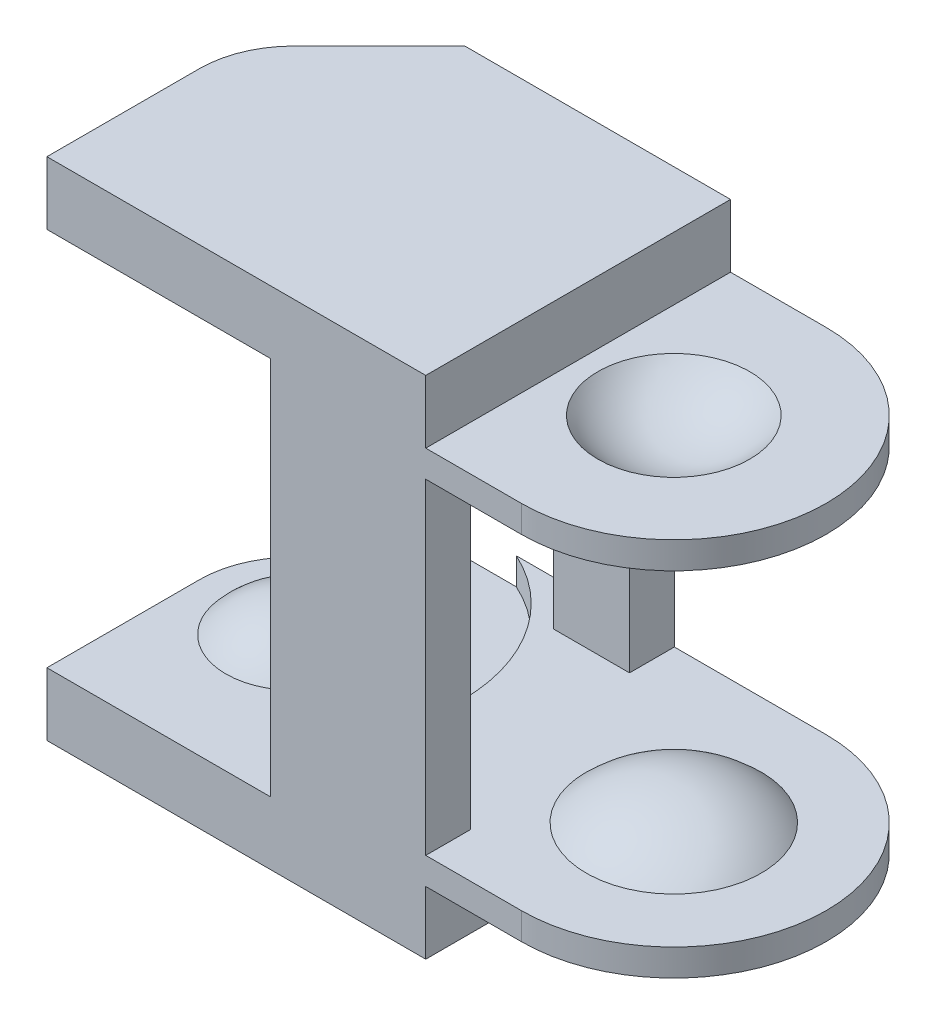
SolidWorks part; units mm, degrees
ref_plane "Front Plane" through (0, 0, 0) normal (0, 0, 1) x (1, 0, 0)
ref_plane "Top Plane" through (0, 0, 0) normal (0, 1, 0) x (1, 0, 0)
ref_plane "Right Plane" through (0, 0, 0) normal (1, 0, 0) x (0, 0, -1)
sketch "Sketch1" plane through (0, 0, 0) normal (0, 0, 1) x (1, 0, 0)
  line L0 (-6.35, 0) -> (6.35, 0)
  line L1 (6.35, 0) -> (6.35, -9.525)
  line L2 (6.35, -9.525) -> (-6.35, -9.525)
  line L3 (-6.35, -9.525) -> (-6.35, 0)
  point P3 (0, -9.525)
  point P6 (0, 0)
  dimension "D1" = 9.525
  dimension "D2" = 12.7
sketch "Sketch3" plane through (0, 0, 0) normal (0, 1, 0) x (1, 0, 0)
  line L0 (6.35, 0) -> (-6.35, 0) construction
  line L1 (-6.35, 0) -> (6.35, 0) construction
  circle A0 centre (-6.35, 3.175) radius 3.175
  circle A1 centre (6.35, 3.175) radius 3.175
  dimension "D1" = 6.35
sketch "Sketch6" plane through (0, 0, 0) normal (0, 1, 0) x (1, 0, 0)
  line L0 (-6.35, 0) -> (-8.1461, 0) construction
  line L1 (-8.1461, 0) -> (-9.0713, 1.5395) construction
  line L2 (3.1496, 3.175) -> (3.1496, 8.2738)
  line L3 (4.5243, 0) -> (3.6069, 1.5264) construction
  line L4 (6.35, 0) -> (-6.35, 0) construction
  line L5 (-6.35, 0) -> (4.5243, 0) construction
  line L6 (-8.1461, 0) -> (-6.9899, -1.9238) construction
  line L7 (-6.9899, -1.9238) -> (3.1496, -1.9238)
  line L8 (5.5675, -1.7359) -> (4.5243, 0) construction
  line L9 (3.1496, 3.175) -> (3.1496, -1.9238)
  line L10 (-8.5951, 5.4201) -> (-5.7413, 8.2738)
  line L11 (-5.7413, 8.2738) -> (3.1496, 8.2738)
  line L12 (-9.525, 3.175) -> (-9.525, -1.9238)
  line L13 (-9.525, -1.9238) -> (-6.9899, -1.9238)
  line L14 (-6.9587, -1.9238) -> (-5.7413, 8.2738) construction
  circle A0 centre (-6.35, 3.175) radius 3.175 construction
  circle A1 centre (6.35, 3.175) radius 3.175 construction
  arc A2 (-8.5951, 5.4201) -> (-9.525, 3.175) centre (-6.35, 3.175) ccw
  arc A4 (3.1496, 3.175) -> (3.6069, 1.5264) centre (6.35, 3.175) ccw construction
  point P21 (-6.35, 3.175)
  dimension "D2" = 0.0254
  dimension "D4" = 45
extrude "Boss-Extrude2" add sketch "Sketch6" along normal blind 2.1082
sketch "Sketch7" plane through (0, 0, 0) normal (0, -1, 0) x (1, 0, 0)
  line L0 (-9.525, 1.9238) -> (3.1496, 1.9238) construction
  line L1 (-2.0506, 1.9238) -> (-2.0506, 0.4238)
  line L6 (6.35, -8.2738) -> (-4.018, -8.2738)
  line L7 (3.1496, -8.2738) -> (-5.7413, -8.2738) construction
  line L8 (3.1496, -8.2738) -> (-5.7413, -8.2738) construction
  line L9 (6.35, 1.9238) -> (-2.0506, 1.9238)
  arc A1 (6.35, -8.2738) -> (6.35, 1.9238) centre (6.35, -3.175) ccw
  arc A2 (-9.525, -3.175) -> (-8.5951, -5.4201) centre (-6.35, -3.175) ccw construction
  arc A3 (-9.525, -3.175) -> (-8.5951, -5.4201) centre (-6.35, -3.175) ccw
  circle A4 centre (-6.35, -3.175) radius 5.0988 construction
  arc A5 (-4.018, -8.2738) -> (-2.0506, 0.4238) centre (-6.35, -3.175) ccw
  dimension "D2" = 0.508
  dimension "D1" = 1.5
extrude "Boss-Extrude3" add sketch "Sketch7" along normal blind 0.9
ref_plane "Plane1" through (0, 0, -3.175) normal (0, 0, 1) x (1, 0, 0)
sketch "Sketch10" plane through (0, 0, -3.175) normal (0, 0, 1) x (1, 0, 0)
  line L0 (-3.175, 0) -> (-9.525, 0) construction
  line L1 (-6.35, 0) -> (-6.35, -1.066)
  line L2 (-6.35, -1.066) -> (-6.35, 0)
  line L3 (-6.35, 0) -> (-4.064, 0)
  line L4 (-4.064, 0) -> (-3.0643, 1.1914) construction
  line L5 (-9.525, 0) -> (-2.0506, 0) construction
  arc A0 (-6.35, -1.066) -> (-4.064, 0) centre (-6.35, 1.9182) ccw
  dimension "D1" = 2.286
  dimension "D2" = 50
revolve "Revolve2" add sketch "Sketch10" angle 360 about L1
sketch "Sketch11" plane through (0, 0, -3.175) normal (0, 0, 1) x (1, 0, 0)
  line L1 (9.525, 0) -> (3.175, 0) construction
  line L2 (8.89, 0) -> (9.5454, 0.781) construction
  line L3 (6.35, -0.9) -> (9.2786, -0.9)
  line L4 (6.35, -0.9) -> (11.4488, -0.9) construction
  line L6 (6.35, -0.9) -> (6.35, -2.0836)
  arc A0 (3.81, 0) -> (8.89, 0) centre (6.35, 2.1313) ccw construction
  arc A3 (6.35, -2.0836) -> (9.2786, -0.9) centre (6.35, 2.1313) ccw
  dimension "D1" = 50
  dimension "D2" = 2.54
  dimension "D3" = 0.8992
sketch "Sketch12" plane through (0, 0, -3.175) normal (0, 0, 1) x (1, 0, 0)
  line L1 (9.525, 0) -> (3.175, 0) construction
  line L2 (8.89, 0) -> (6.35, 0)
  line L3 (6.35, 0) -> (6.35, -1.1844)
  arc A0 (3.81, 0) -> (8.89, 0) centre (6.35, 2.1313) ccw construction
  arc A1 (6.35, -1.1844) -> (8.89, 0) centre (6.35, 2.1313) ccw
revolve "Revolve4" add sketch "Sketch11" angle 360 about L6
revolve "Cut-Revolve1" cut sketch "Sketch12" angle 360 about L3
sketch "Sketch13" plane through (0, 0, 0) normal (0, -1, 0) x (1, 0, 0)
  line L1 (6.35, 1.9238) -> (-2.0506, 1.9238) construction
  line L2 (-2.0506, 0.4238) -> (3.1496, 0.4238)
  line L3 (-2.0506, 0.4238) -> (-2.0506, 1.9238)
  line L4 (-2.0506, 1.9238) -> (3.1496, 1.9238)
  line L5 (3.1496, 0.4238) -> (3.1496, 1.9238)
  line L6 (-2.0506, 0.4238) -> (3.1496, 1.9238) construction
  line L8 (-2.0506, 1.9238) -> (3.1496, 0.4238) construction
  arc A0 (-4.018, -8.2738) -> (-2.0506, 0.4238) centre (-6.35, -3.175) ccw construction
  point P0 (0.5495, 1.1738)
extrude "Boss-Extrude4" add sketch "Sketch13" along normal blind 6.35
sketch "Sketch16" plane through (0, -0.9, 0) normal (0, -1, 0) x (1, 0, 0)
  line L0 (-4.018, -8.2738) -> (6.35, -8.2738) construction
  line L1 (1.27, -8.2738) -> (-1.27, -8.2738)
  line L2 (1.27, -8.2738) -> (1.27, -6.7738)
  line L3 (1.27, -6.7738) -> (-1.27, -6.7738)
  line L4 (-1.27, -8.2738) -> (-1.27, -6.7738)
  line L5 (3.1496, 0.4238) -> (3.1496, 1.9238) construction
  point P8 (0, -6.7738)
  dimension "D1" = 2.54
extrude "Boss-Extrude5" add sketch "Sketch16" along normal up to vertex (5.45 mm away) up to point (3.1496, -6.35, 0.4238)
mirror "Mirror1" about plane through (3.1496, -6.35, 1.9238) normal (0, 1, 0) of bodies 117 110 114
